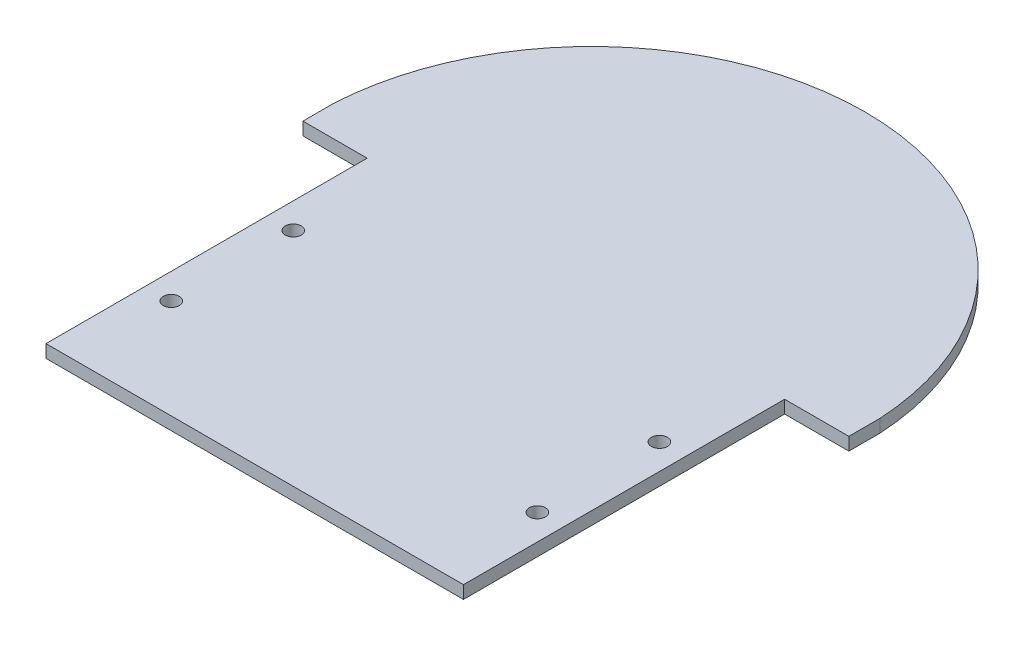
SolidWorks part; units mm, degrees
ref_plane "Front Plane" through (0, 0, 0) normal (0, 0, 1) x (1, 0, 0)
ref_plane "Top Plane" through (0, 0, 0) normal (0, 1, 0) x (1, 0, 0)
ref_plane "Right Plane" through (0, 0, 0) normal (1, 0, 0) x (0, 0, -1)
sketch "Sketch1" plane through (0, 0, 0) normal (0, 1, 0) x (1, 0, 0)
  line L0 (-99.0435, 0) -> (261.2826, 0) construction
  line L1 (-42.5, -47.5) -> (42.5, -47.5)
  line L2 (-42.5, -47.5) -> (-42.5, 47.5)
  line L3 (-42.5, 47.5) -> (42.5, 47.5)
  line L4 (42.5, -47.5) -> (42.5, 47.5)
  line L5 (-42.5, -47.5) -> (42.5, 47.5) construction
  line L6 (-42.5, 47.5) -> (42.5, -47.5) construction
  line L7 (0, 116.7826) -> (0, -137.4783) construction
  line L8 (42.5, 2.5) -> (32.5, 2.5)
  line L9 (-42.5, -47.5) -> (-32.5, -47.5)
  line L10 (-42.5, -47.5) -> (-42.5, 2.5)
  line L11 (-42.5, 2.5) -> (-32.5, 2.5)
  line L12 (-32.5, -47.5) -> (-32.5, 2.5)
  line L13 (32.5, -47.5) -> (32.5, 2.5)
  line L14 (42.5, -47.5) -> (32.5, -47.5)
  line L15 (42.5, -47.5) -> (42.5, 2.5)
  arc A0 (-42.5, 2.5) -> (42.5, 2.5) centre (0, 4.9306) cw
  point P0 (0, 0)
  dimension "D1" = 85
  dimension "D2" = 95
  dimension "D3" = 10
  dimension "D4" = 50
extrude "Boss-Extrude1" add sketch "Sketch1" along normal blind 2 contours A0 L2 L11 L12 L1 L13 L8 L4
sketch "Sketch2" plane through (0, 0, 0) normal (0, 1, 0) x (1, 0, 0)
  line L0 (0, 96.4443) -> (0, -98.7226) construction
  line L1 (-116.5686, 0) -> (171.6254, 0) construction
  line L3 (-28.5, 65.0059) -> (-28.5, -103.839) construction
  line L4 (28.5, 65.0059) -> (28.5, -103.839) construction
  line L5 (-116.5686, -22.5) -> (96.3112, -22.5) construction
  line L6 (-42.5, 2.5) -> (-32.5, 2.5) construction
  line L7 (-32.5, -47.5) -> (-32.5, 2.5) construction
  line L9 (-116.5686, -13) -> (105.7864, -13) construction
  line L10 (-116.5686, -32) -> (105.7864, -32) construction
  circle A0 centre (-28.5, -13) radius 1.25
  circle A1 centre (-28.5, -32) radius 1.25
  circle A2 centre (28.5, -32) radius 1.25
  circle A3 centre (28.5, -13) radius 1.25
  dimension "D5" = 2.5
  dimension "D1" = 25
  dimension "D2" = 50
  dimension "D3" = 4
  dimension "D4" = 9.5
extrude "Cut-Extrude1" cut sketch "Sketch2" along normal blind 2
